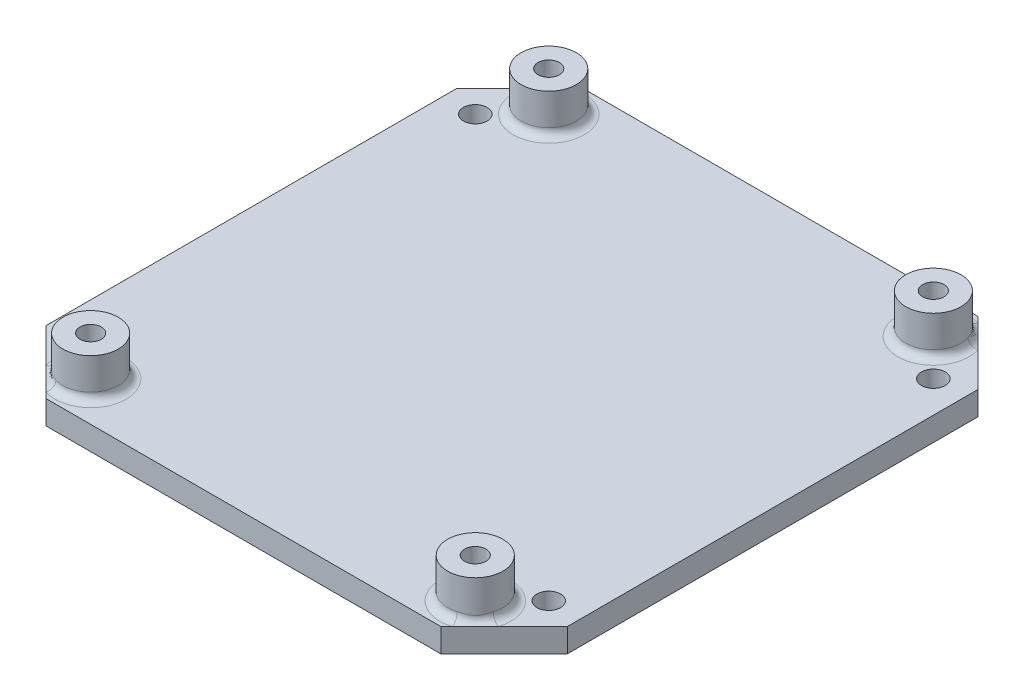
SolidWorks part; units mm, degrees
ref_plane "前视基准面" through (0, 0, 0) normal (0, 0, 1) x (1, 0, 0)
ref_plane "上视基准面" through (0, 0, 0) normal (0, 1, 0) x (1, 0, 0)
ref_plane "右视基准面" through (0, 0, 0) normal (1, 0, 0) x (0, 0, -1)
other "Configuration Table"
sketch "草图1" plane through (0, 0, 0) normal (0, 1, 0) x (1, 0, 0)
  line L0 (0, 0) -> (0, 34) construction
  line L1 (-29, -24.35) -> (29, -24.35) construction
  line L2 (-29, -24.35) -> (-29, 24.35) construction
  line L3 (-29, 24.35) -> (29, 24.35) construction
  line L4 (29, -24.35) -> (29, 24.35) construction
  line L5 (-29, -24.35) -> (29, 24.35) construction
  line L6 (-29, 24.35) -> (29, -24.35) construction
  line L7 (24.35, -29) -> (-24.35, -29) construction
  line L8 (24.35, -29) -> (24.35, 29) construction
  line L9 (24.35, 29) -> (-24.35, 29) construction
  line L10 (-24.35, -29) -> (-24.35, 29) construction
  line L11 (24.35, -29) -> (-24.35, 29) construction
  line L12 (24.35, 29) -> (-24.35, -29) construction
  line L13 (-33, 34) -> (33, 34)
  line L14 (-33, 34) -> (-33, -34)
  line L15 (-33, -34) -> (33, -34)
  line L16 (33, 34) -> (33, -34)
  circle A0 centre (-29, 24.35) radius 1.5
  circle A1 centre (29, 24.35) radius 1.5
  circle A2 centre (29, -24.35) radius 1.5
  circle A3 centre (-29, -24.35) radius 1.5
  circle A4 centre (-24.35, 29) radius 3
  circle A5 centre (24.35, 29) radius 3
  circle A6 centre (-24.35, -29) radius 3
  circle A7 centre (24.35, -29) radius 3
  point P0 (0, 0)
  point P10 (0, 0)
  point P23 (33, 33.2207)
  dimension "D3" = 3
  dimension "D6" = 6
  dimension "D1" = 48.7
  dimension "D2" = 58
  dimension "D4" = 48.7
  dimension "D5" = 58
  dimension "D7" = 4
  dimension "D8" = 5
  dimension "D9" = 5
extrude "凸台-拉伸1" add sketch "草图1" along normal blind 3
sketch "草图2" plane through (0, 3, 0) normal (0, 1, 0) x (1, 0, 0)
  line L0 (33, 0) -> (0, 0) construction
  line L1 (33, -34) -> (33, 34) construction
  line L2 (0, 0) -> (0, 34) construction
  line L3 (33, 34) -> (-33, 34) construction
  circle A0 centre (-24.35, 29) radius 3.5
  circle A1 centre (-24.35, 29) radius 1.35
  circle A9 centre (24.35, 29) radius 1.35
  circle A10 centre (24.35, 29) radius 3.5
  circle A11 centre (24.35, -29) radius 3.5
  circle A12 centre (24.35, -29) radius 1.35
  circle A13 centre (-24.35, -29) radius 1.35
  circle A14 centre (-24.35, -29) radius 3.5
  point P4 (-24.35, 29)
  dimension "D1" = 2.7
  dimension "D2" = 7
extrude "凸台-拉伸2" add sketch "草图2" along normal blind 5
chamfer "倒角1" distance 8 angle 45 4 edges at (33, 1.5, -34) (-33, 1.5, -34) (33, 1.5, 34) (-33, 1.5, 34)
fillet "圆角2" radius 1 4 edges at (-24.35, 3, 25.5) (24.35, 3, 32.5) (24.35, 3, -32.5) (-24.35, 3, -25.5)
